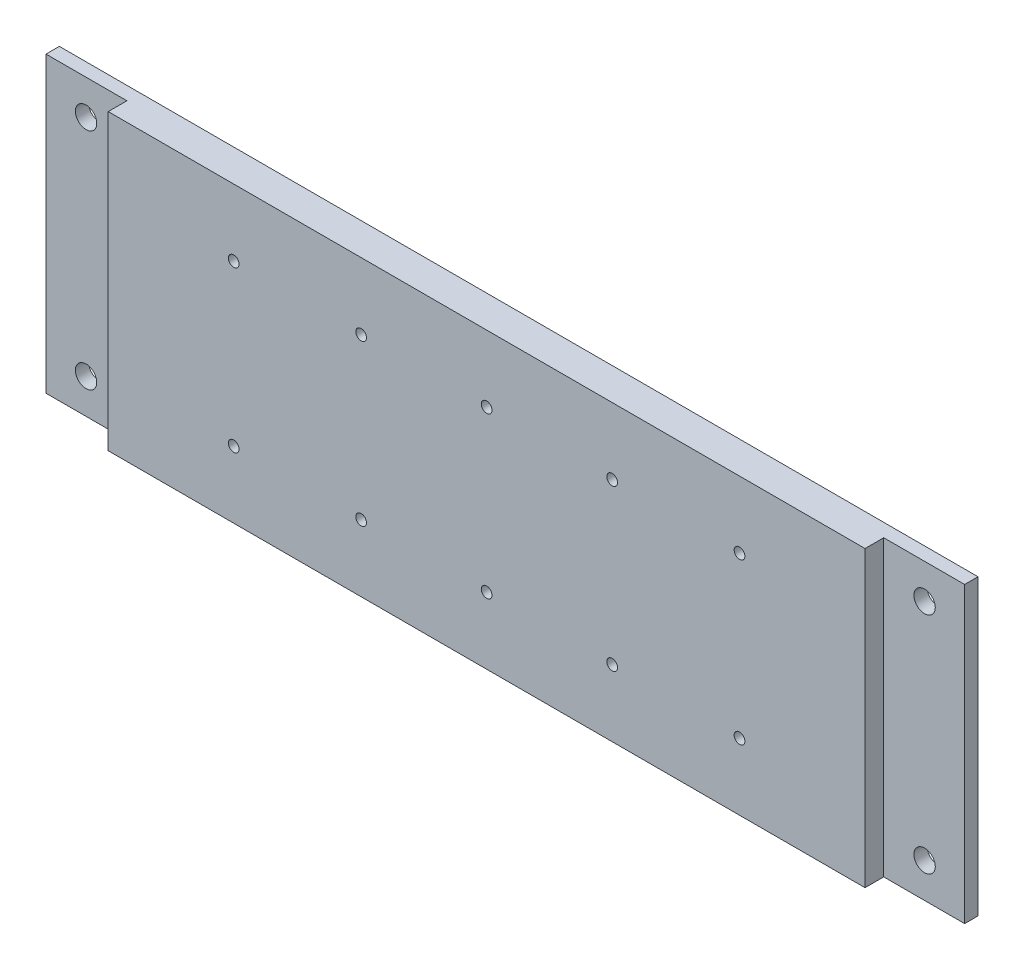
SolidWorks part; units mm, degrees
ref_plane "Plan de face" through (0, 0, 0) normal (0, 0, 1) x (1, 0, 0)
ref_plane "Plan de dessus" through (0, 0, 0) normal (0, 1, 0) x (1, 0, 0)
ref_plane "Plan de droite" through (0, 0, 0) normal (1, 0, 0) x (0, 0, -1)
sketch "Esquisse1" plane through (0, 0, 0) normal (0, 0, 1) x (1, 0, 0)
  line L1 (-86, 27.5) -> (86, 27.5)
  line L2 (-86, 27.5) -> (-86, -27.5)
  line L3 (-86, -27.5) -> (86, -27.5)
  line L4 (86, 27.5) -> (86, -27.5)
  line L5 (-86, 27.5) -> (86, -27.5) construction
  line L6 (-86, -27.5) -> (86, 27.5) construction
  point P0 (0, 0)
  dimension "D1" = 172
  dimension "D2" = 55
extrude "Boss.-Extru.1" add sketch "Esquisse1" along normal blind 6
sketch "Esquisse2" plane through (0, 0, 6) normal (0, 0, 1) x (1, 0, 0)
  line L0 (-86, -27.5) -> (86, -27.5) construction
  line L1 (-86, 27.5) -> (-70.85, 27.5)
  line L2 (-86, 27.5) -> (-86, -27.5)
  line L3 (-86, -27.5) -> (-70.85, -27.5)
  line L4 (-70.85, 27.5) -> (-70.85, -27.5)
  line L5 (0, 27.5) -> (0, -27.5) construction
  line L6 (86, 27.5) -> (-86, 27.5) construction
  line L7 (86, -27.5) -> (70.85, -27.5)
  line L8 (86, 27.5) -> (86, -27.5)
  line L9 (70.85, 27.5) -> (70.85, -27.5)
  line L10 (86, 27.5) -> (70.85, 27.5)
  dimension "D1" = 15.15
extrude "Enlèv. mat.-Extru.1" cut sketch "Esquisse2" against normal blind 3.5
sketch "Esquisse3" plane through (0, 0, 2.5) normal (0, 0, 1) x (1, 0, 0)
  line L0 (0, -27.5) -> (0, 27.5) construction
  line L1 (-86, 0) -> (86, 0) construction
  line L2 (-86, 27.5) -> (-86, -27.5) construction
  line L3 (86, -27.5) -> (86, 27.5) construction
  line L4 (70.85, 27.5) -> (-70.85, 27.5) construction
  line L5 (-70.85, -27.5) -> (70.85, -27.5) construction
  circle A0 centre (-78.5, 21) radius 2
  circle A1 centre (-78.5, -21) radius 2
  circle A2 centre (78.5, -21) radius 2
  circle A3 centre (78.5, 21) radius 2
  dimension "D1" = 21
  dimension "D2" = 4
  dimension "D3" = 78.5
extrude "Enlèv. mat.-Extru.2" cut sketch "Esquisse3" against normal through all
sketch "Esquisse4" plane through (0, 0, 6) normal (0, 0, 1) x (1, 0, 0)
  line L0 (-86, 0) -> (86, 0) construction
  line L1 (-86, 27.5) -> (-86, -27.5) construction
  line L2 (86, -27.5) -> (86, 27.5) construction
  line L3 (-70.85, -27.5) -> (-70.85, 27.5) construction
  line L4 (70.85, 27.5) -> (-70.85, 27.5) construction
  line L5 (0, 27.5) -> (0, -27.5) construction
  line L6 (-70.85, -27.5) -> (70.85, -27.5) construction
  line L8 (-70.85, -27.5) -> (-70.85, 27.5) construction
  line L9 (-70.85, 15) -> (70.85, 15) construction
  line L10 (70.85, 27.5) -> (70.85, -27.5) construction
  circle A0 centre (-47.35, 15) radius 1.005
  circle A1 centre (-23.5, 15) radius 1.005
  circle A2 centre (23.5, 15) radius 1.005
  circle A3 centre (47.35, 15) radius 1.005
  circle A4 centre (47.35, -15) radius 1.005
  circle A5 centre (23.5, -15) radius 1.005
  circle A6 centre (-23.5, -15) radius 1.005
  circle A7 centre (-47.35, -15) radius 1.005
  circle A8 centre (0, 15) radius 1.005
  circle A9 centre (0, -15) radius 1.005
  dimension "D1" = 2.01
  dimension "D2" = 2.01
  dimension "D6" = 2.01
  dimension "D3" = 23.5
  dimension "D4" = 23.5
  dimension "D5" = 15
  dimension "D7" = 23.85
extrude "Enlèv. mat.-Extru.3" cut sketch "Esquisse4" against normal through all
